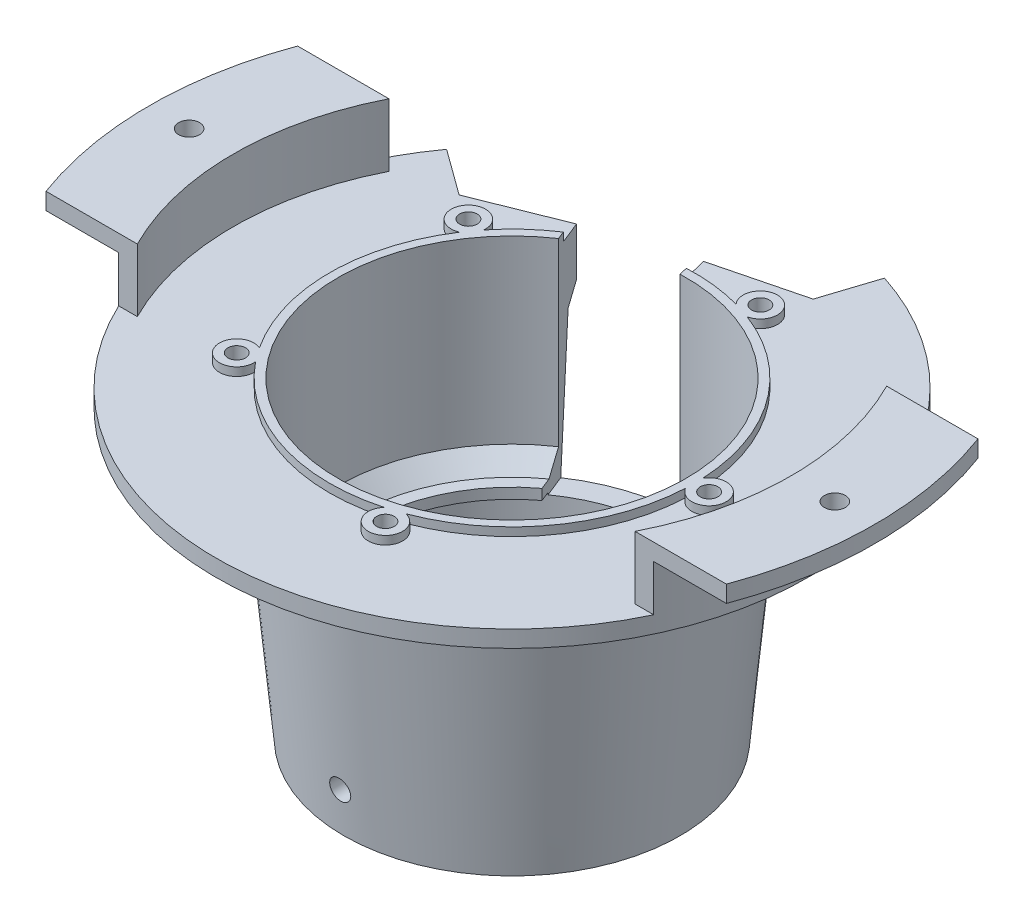
SolidWorks part; units mm, degrees
ref_plane "Front Plane" through (0, 0, 0) normal (0, 0, 1) x (1, 0, 0)
ref_plane "Top Plane" through (0, 0, 0) normal (0, 1, 0) x (1, 0, 0)
ref_plane "Right Plane" through (0, 0, 0) normal (1, 0, 0) x (0, 0, -1)
sketch "Sketch1" plane through (0, 0, 0) normal (0, 0, 1) x (1, 0, 0)
  line L26 (-70.5, -4) -> (-70.5, 11)
  line L27 (-70.5, 11) -> (-86.5, 11)
  line L28 (-86.5, 11) -> (-86.5, 15)
  line L29 (-86.5, 15) -> (-66.5, 15)
  line L30 (-66.5, 15) -> (-66.5, 0)
  line L31 (-66.5, 0) -> (-41.5, 0)
  line L36 (-37.1, -47.5) -> (-37.1, -72.5)
  line L37 (-37.1, -72.5) -> (-40.1, -72.5)
  line L38 (-37.5, -45) -> (-34.6, -45)
  line L42 (-41.5, 0) -> (-41.5, -41)
  line L43 (-34.6, -45) -> (-34.6, -47.5)
  line L44 (-34.6, -47.5) -> (-37.1, -47.5)
  line L45 (-70.5, -4) -> (-56.5, -4)
  line L47 (-45.5, -15) -> (-40.1, -72.5)
  line L48 (-56.5, -4) -> (-45.5, -15)
  line L49 (-37.5, -45) -> (-41.5, -41)
  dimension "D2" = 45
  dimension "D3" = 2.5
  dimension "D4" = 41.5
  dimension "D5" = 135
  dimension "D6" = 2.5
  dimension "D7" = 15
  dimension "D8" = 4
  dimension "D9" = 37.1
  dimension "D10" = 3
  dimension "D11" = 20
  dimension "D12" = 4
  dimension "D13" = 4
  dimension "D14" = 25
  dimension "D15" = 4
  dimension "D16" = 25
  dimension "D17" = 15
  dimension "D18" = 15
  dimension "D19" = 4
ref_axis "Axis1" through (0, -100.5, 0) along (0, 1, 0)
revolve "Revolve1" add sketch "Sketch1" angle 360 about axis through (0, -100.5, 0) along (0, 1, 0)
sketch "Sketch2" plane through (0, 11, 0) normal (0, -1, 0) x (1, 0, 0)
  circle A0 centre (77, 0) radius 2.5
  circle A1 centre (-77, 0) radius 2.5
  dimension "D1" = 5
  dimension "D3" = 77
  dimension "D2" = 77
extrude "Cut-Extrude3" cut sketch "Sketch2" against normal up to surface (4 mm away) up to face at (0, 15, -86.5)
sketch "Sketch3" plane through (0, 15, 0) normal (0, 1, 0) x (1, 0, 0)
  line L0 (-59.3485, -30) -> (-81.1311, -30)
  line L1 (81.1311, -30) -> (59.3485, -30)
  line L5 (81.1311, 30) -> (59.3485, 30)
  line L9 (-59.3485, 30) -> (-81.1311, 30)
  circle A0 centre (0, 0) radius 86.5 construction
  circle A1 centre (-77, 0) radius 2.5 construction
  arc A2 (-81.1311, -30) -> (81.1311, -30) centre (0, 0) ccw
  circle A3 centre (0, 0) radius 66.5 construction
  arc A4 (-59.3485, -30) -> (59.3485, -30) centre (0, 0) ccw
  arc A5 (59.3485, 30) -> (-59.3485, 30) centre (0, 0) ccw
  arc A6 (81.1311, 30) -> (-81.1311, 30) centre (0, 0) ccw
  dimension "D2" = 30
  dimension "D1" = 30
extrude "Cut-Extrude4" cut sketch "Sketch3" against normal up to surface (15 mm away) up to face at (0, 0, -66.5)
sketch "Sketch6" plane through (0, 0, 0) normal (0, 0, 1) x (1, 0, 0)
  line L0 (0, -100.5) -> (0, 20.5) construction
  line L2 (-40.1, -72.5) -> (40.1, -72.5) construction
  circle A0 centre (0, -62.5) radius 2.5
  dimension "D1" = 5
  dimension "D2" = 10
extrude "Cut-Extrude6" cut sketch "Sketch6" against normal through all both and the other way through all
sketch "Sketch7" plane through (0, 0, 0) normal (0, 1, 0) x (1, 0, 0)
  circle A0 centre (47, 0) radius 2.1
  dimension "D1" = 4.2
  dimension "D2" = 47
extrude "Cut-Extrude7" cut sketch "Sketch7" against normal up to surface (13.4531 mm away) contours A0
pattern_circular "CirPattern1" count 5 every 72 about axis through (0, 0, 0) along (0, 1, 0) of "Cut-Extrude7"
sketch "Sketch8" plane through (0, 0, 0) normal (0, 1, 0) x (1, 0, 0)
  circle A0 centre (0, 0) radius 41.5 construction
  circle A1 centre (0, 0) radius 41.5
  arc A2 (-33.9458, -27.2017) -> (-17.3102, -39.9075) centre (0, 0) ccw
  circle A3 centre (-38.0238, -27.6259) radius 2.1 construction
  circle A4 centre (14.5238, -44.6997) radius 2.1 construction
  circle A5 centre (47, 0) radius 2.1 construction
  circle A6 centre (14.5238, 44.6997) radius 2.1 construction
  circle A7 centre (-38.0238, 27.6259) radius 2.1 construction
  circle A8 centre (-38.0238, -27.6259) radius 2.1
  circle A9 centre (14.5238, -44.6997) radius 2.1
  circle A10 centre (47, 0) radius 2.1
  circle A11 centre (14.5238, 44.6997) radius 2.1
  circle A12 centre (-38.0238, 27.6259) radius 2.1
  arc A13 (-33.9458, 27.2017) -> (-36.3602, 23.8786) centre (-38.0238, 27.6259) ccw
  arc A14 (15.3805, 40.6902) -> (11.474, 41.9595) centre (14.5238, 44.6997) ccw
  arc A15 (43.4515, -2.0538) -> (43.4515, 2.0538) centre (47, 0) ccw
  arc A16 (11.474, -41.9595) -> (15.3805, -40.6902) centre (14.5238, -44.6997) ccw
  arc A17 (-36.3602, -23.8786) -> (-33.9458, -27.2017) centre (-38.0238, -27.6259) ccw
  arc A18 (15.3805, -40.6902) -> (43.4515, -2.0538) centre (0, 0) ccw
  circle A19 centre (-38.0238, -27.6259) radius 4.1 construction
  circle A20 centre (0, 0) radius 43.5 construction
  circle A21 centre (14.5238, -44.6997) radius 4.1 construction
  arc A22 (43.4515, 2.0538) -> (15.3805, 40.6902) centre (0, 0) ccw
  arc A23 (11.474, 41.9595) -> (-33.9458, 27.2017) centre (0, 0) ccw
  circle A24 centre (47, 0) radius 4.1 construction
  arc A25 (-36.3602, 23.8786) -> (-36.3602, -23.8786) centre (0, 0) ccw
  circle A26 centre (14.5238, 44.6997) radius 4.1 construction
  circle A27 centre (-38.0238, 27.6259) radius 4.1 construction
  arc A33 (-17.3102, -39.9075) -> (11.474, -41.9595) centre (0, 0) ccw
  point P4 (18.6238, -44.6997)
  point P23 (-33.9238, 27.6259)
  point P29 (41.5993, 12.7182)
  point P30 (-33.9238, -27.6259)
  point P39 (51.1, 0)
  point P42 (18.6238, 44.6997)
  point P49 (-16.377, -50.4063)
  point P57 (-8.777, -50.4063)
  dimension "D1" = 2
  dimension "D2" = 2
extrude "Boss-Extrude1" add sketch "Sketch8" along normal blind 2
sketch "Sketch9" plane through (0, 2, 0) normal (0, 1, 0) x (1, 0, 0)
  line L0 (-26.114, 41.5038) -> (-46.114, 33.5038)
  line L1 (-46.114, 33.5038) -> (-57.0357, 41.4389)
  line L2 (-57.0357, 41.4389) -> (-45.8058, 62.9454)
  line L3 (0, 0) -> (-26.114, 80.3707) construction
  line L4 (-45.8058, 62.9454) -> (-23.2656, 71.6041)
  line L5 (0, 0) -> (-38.0238, 27.6259) construction
  line L6 (-26.114, 41.5038) -> (-18.5619, 22.6237)
  line L7 (-18.5619, 22.6237) -> (1.7191, 29.2134)
  line L8 (-3.2687, 48.9267) -> (1.7191, 29.2134)
  line L9 (-3.2687, 48.9267) -> (17.614, 54.2102)
  line L10 (17.614, 54.2102) -> (21.7857, 67.0495)
  line L11 (21.7857, 67.0495) -> (0.0593, 77.8479)
  line L12 (0.0593, 77.8479) -> (-23.2656, 71.6041)
  point P3 (-8.4214, 25.9185)
  point P10 (-15.7151, 48.3662)
  dimension "D1" = 10
  dimension "D2" = 20
  dimension "D3" = 8
extrude "Cut-Extrude8" cut sketch "Sketch9" against normal blind 50 and the other way through all
